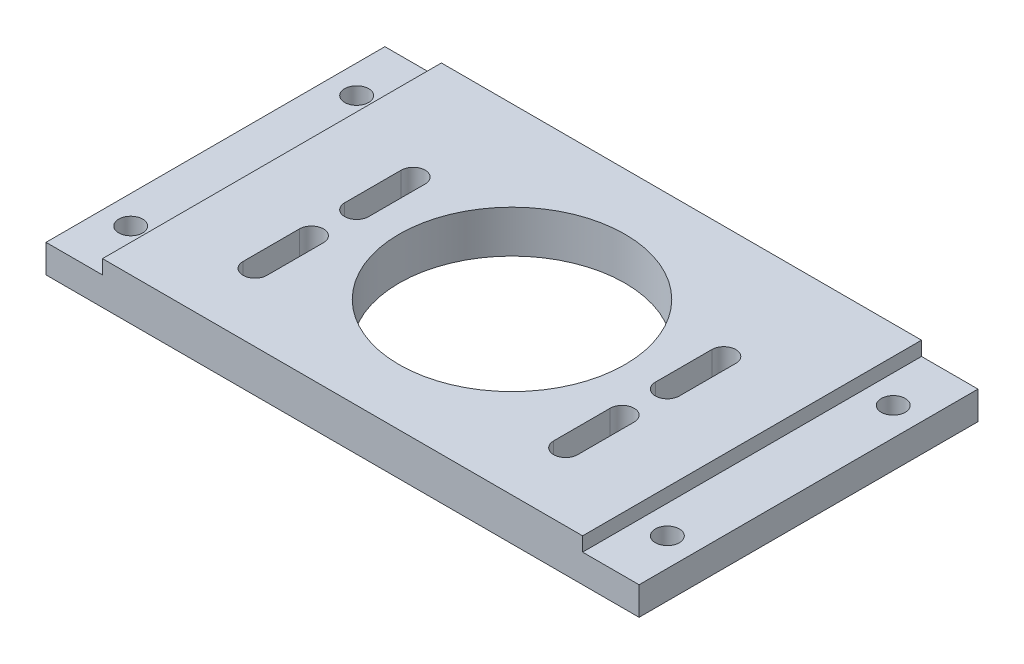
SolidWorks part; units mm, degrees
ref_plane "前视基准面" through (0, 0, 0) normal (0, 0, 1) x (1, 0, 0)
ref_plane "上视基准面" through (0, 0, 0) normal (0, 1, 0) x (1, 0, 0)
ref_plane "右视基准面" through (0, 0, 0) normal (1, 0, 0) x (0, 0, -1)
sketch "草图1" plane through (0, 0, 0) normal (0, 0, 1) x (1, 0, 0)
  line L1 (0, 0) -> (210, 0)
  line L2 (0, 0) -> (0, 10)
  line L3 (20, 15) -> (190, 15)
  line L4 (210, 0) -> (210, 10)
  line L7 (0, 10) -> (20, 10)
  line L8 (20, 15) -> (20, 10)
  line L11 (210, 10) -> (190, 10)
  line L12 (190, 15) -> (190, 10)
  dimension "D1" = 210
  dimension "D2" = 15
  dimension "D3" = 20
  dimension "D4" = 5
extrude "拉伸1" add sketch "草图1" along normal blind 120
hole_wizard "Ø8.5 (8.5) 直径孔1" positions "3D草图1" profile "草图2" hole size "Ø8.5" standard "GB" end condition through all
sketch3d "3D草图1"
  point P0 (10, 0, 20)
sketch "草图2" plane through (10, 0, 20) normal (1, 0, 0) x (0, 0, -1)
  line L0 (0, 0) -> (0, 15)
  line L1 (0, 15) -> (4.25, 15)
  line L2 (4.25, 15) -> (4.25, 0)
  line L5 (4.25, 0) -> (0, 0)
  line L11 (0, -6.35) -> (0, 107.95) construction
  dimension "通孔孔直径" = 8.5
  dimension "通孔孔深度" = 15
pattern_linear "阵列(线性)1" count 2 spacing 190 along (1, 0, 0) count 2 spacing 80 along (0, 0, 1) of "Ø8.5 (8.5) 直径孔1"
sketch "草图3" plane through (0, 0, 0) normal (0, -1, 0) x (1, 0, 0)
  line L0 (45.75, 96) -> (45.75, 76)
  line L1 (54.25, 96) -> (54.25, 76)
  line L3 (155.75, 96) -> (155.75, 76)
  line L4 (164.25, 96) -> (164.25, 76)
  line L5 (45.75, 60) -> (45.75, 40)
  line L6 (54.25, 60) -> (54.25, 40)
  line L7 (155.75, 60) -> (155.75, 40)
  line L8 (164.25, 60) -> (164.25, 40)
  line L9 (0, 120) -> (0, 0) construction
  line L10 (0, 120) -> (210, 120) construction
  circle A0 centre (105, 60) radius 40
  arc A1 (54.25, 96) -> (45.75, 96) centre (50, 96) ccw
  arc A2 (45.75, 76) -> (54.25, 76) centre (50, 76) ccw
  arc A3 (164.25, 96) -> (155.75, 96) centre (160, 96) ccw
  arc A4 (155.75, 76) -> (164.25, 76) centre (160, 76) ccw
  arc A5 (54.25, 60) -> (45.75, 60) centre (50, 60) ccw
  arc A6 (45.75, 40) -> (54.25, 40) centre (50, 40) ccw
  arc A7 (164.25, 60) -> (155.75, 60) centre (160, 60) ccw
  arc A8 (155.75, 40) -> (164.25, 40) centre (160, 40) ccw
  point P3 (45.75, 86)
  dimension "D1" = 8.5
  dimension "D2" = 8.5
  dimension "D3" = 20
  dimension "D5" = 55
  dimension "D6" = 105
  dimension "D7" = 60
  dimension "D4" = 26
  dimension "D8" = 110
  dimension "D9" = 36
extrude "拉伸2" cut sketch "草图3" against normal up to next
